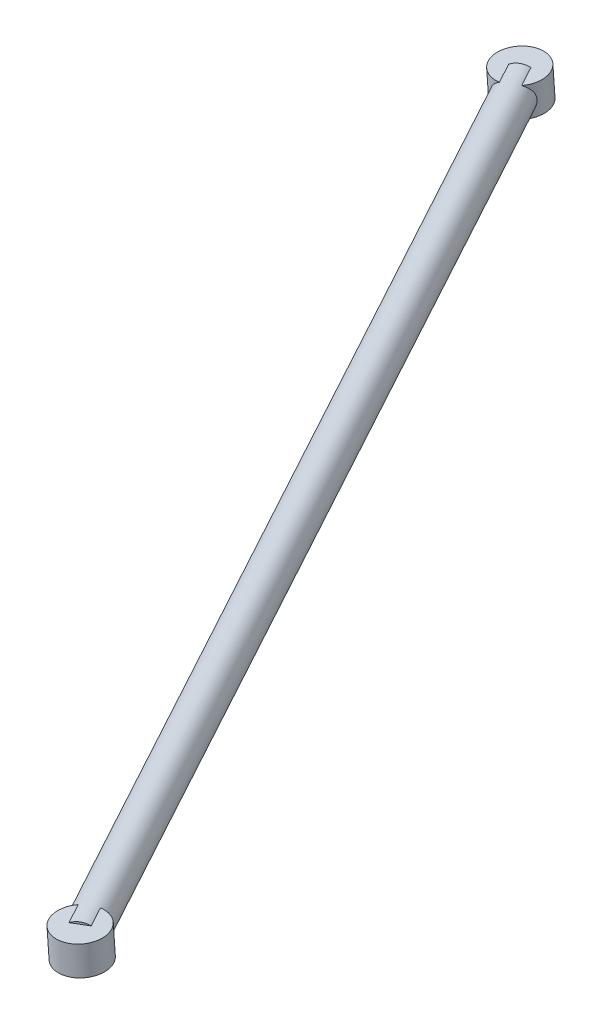
SolidWorks part; units mm, degrees
ref_plane "Plano frontal" through (0, 0, 0) normal (0, 0, 1) x (1, 0, 0)
ref_plane "Plano superior" through (0, 0, 0) normal (0, 1, 0) x (1, 0, 0)
ref_plane "Plano direito" through (0, 0, 0) normal (1, 0, 0) x (0, 0, -1)
sketch3d "SUSP_FR_pushrod_eixo"
  line L0 (535.6, -114.51, -83.23) -> (308.5607, -96.2566, -516.2583)
sweep "SUSP_FR_pushrod" add path "SUSP_FR_pushrod_eixo" circular profile diameter 16 parameters "D3"=16
sketch3d "SUSP_FR_pushrod_rod_end_mount_eixo"
  line L0 (535.4642, -107.5209, -82.8639) -> (535.7358, -121.4991, -83.5961)
sweep "SUSP_FR_pushrod_rod_end_mount" add path "SUSP_FR_pushrod_rod_end_mount_eixo" circular profile diameter 22 parameters "D3"=22
sketch3d "SUSP_FR_pushrod_rod_end_rocker_eixo"
  line L0 (308.4249, -89.2675, -515.8922) -> (308.6965, -103.2457, -516.6244)
sweep "SUSP_FR_pushrod_rod_end_rocker" add path "SUSP_FR_pushrod_rod_end_rocker_eixo" circular profile diameter 22 parameters "D3"=22
sketch3d "REF_SKETCH"
  line L0 (531.6, -116.91, -85.03) -> (539.6, -112.11, -81.43)
  line L1 (538, -117.51, -86.43) -> (533.2, -111.51, -80.03)
  line L2 (304.5607, -98.6566, -518.0583) -> (312.5607, -93.8566, -514.4583)
  line L3 (310.9607, -99.2566, -519.4583) -> (306.1607, -93.2566, -513.0583)
ref_point "P_MOUNT"
ref_point "P_ROCKER"
